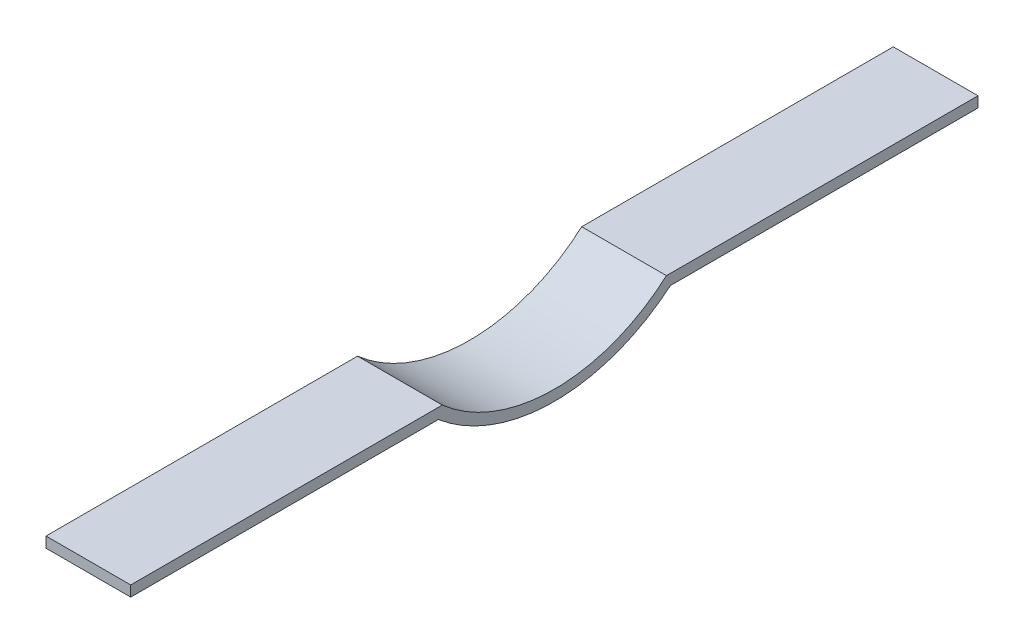
SolidWorks part; units mm, degrees
ref_plane "Front Plane" through (0, 0, 0) normal (0, 0, 1) x (1, 0, 0)
ref_plane "Top Plane" through (0, 0, 0) normal (0, 1, 0) x (1, 0, 0)
ref_plane "Right Plane" through (0, 0, 0) normal (1, 0, 0) x (0, 0, -1)
sketch "Sketch1" plane through (0, 0, 0) normal (1, 0, 0) x (0, 0, -1)
  line L0 (-76.4641, -76.2) -> (-67.2021, -76.2)
  line L1 (67.2021, -76.2) -> (76.4641, -76.2)
  arc A0 (67.2021, -76.2) -> (-67.2021, -76.2) centre (0, 0) cw
  arc A1 (76.4641, -76.2) -> (-76.4641, -76.2) centre (0, 0) cw
  dimension "D1" = 101.6
  dimension "D2" = 107.95
  dimension "D3" = 76.2
extrude "Boss-Extrude1" add sketch "Sketch1" along normal mid plane 50.8
ref_plane "Plane1" through (0, 0, 254) normal (0, 0, 1) x (1, 0, 0)
sketch "Sketch2" plane through (0, 0, 254) normal (0, 0, 1) x (1, 0, 0)
  line L0 (25.4, -107.95) -> (25.4, -76.2) construction
  line L1 (-25.4, -76.2) -> (25.4, -76.2)
  line L2 (-25.4, -76.2) -> (-25.4, -82.55)
  line L3 (-25.4, -82.55) -> (25.4, -82.55)
  line L4 (25.4, -76.2) -> (25.4, -82.55)
  dimension "D1" = 6.35
extrude "Boss-Extrude2" add sketch "Sketch2" against normal up to body separate body
mirror "Mirror1" about plane through (0, 0, 0) normal (0, 0, 1) of "Boss-Extrude2"
sketch "Sketch3" [suppressed] plane through (0, -44.45, 0) normal (0, -1, 0) x (1, 0, 0)
  line L0 (25.4, 98.3738) -> (25.4, 254) construction
  line L1 (-25.4, 254) -> (25.4, 254)
  line L2 (-25.4, 254) -> (-25.4, 247.65)
  line L3 (-25.4, 247.65) -> (25.4, 247.65)
  line L4 (25.4, 254) -> (25.4, 247.65)
  dimension "D1" = 6.35
extrude "Boss-Extrude3" [suppressed] add sketch "Sketch3" along normal blind 25.4
mirror "Mirror2" [suppressed] about plane through (0, 0, 0) normal (0, 0, 1)
sketch "Sketch4" [suppressed] plane through (0, -44.45, 0) normal (0, -1, 0) x (1, 0, 0)
  line L0 (-25.4, 254) -> (25.4, 254) construction
  line L1 (-12.7, 254) -> (12.7, 254)
  line L2 (-12.7, 254) -> (-12.7, 260.35)
  line L3 (-12.7, 260.35) -> (12.7, 260.35)
  line L4 (12.7, 254) -> (12.7, 260.35)
  line L5 (25.4, 98.3738) -> (25.4, 254) construction
  dimension "D1" = 25.4
  dimension "D2" = 6.35
  dimension "D3" = 12.7
extrude "Boss-Extrude4" [suppressed] add sketch "Sketch4" against normal up to surface (6.35 mm away)
mirror "Mirror3" [suppressed] about plane through (0, 0, 0) normal (0, 0, 1)
